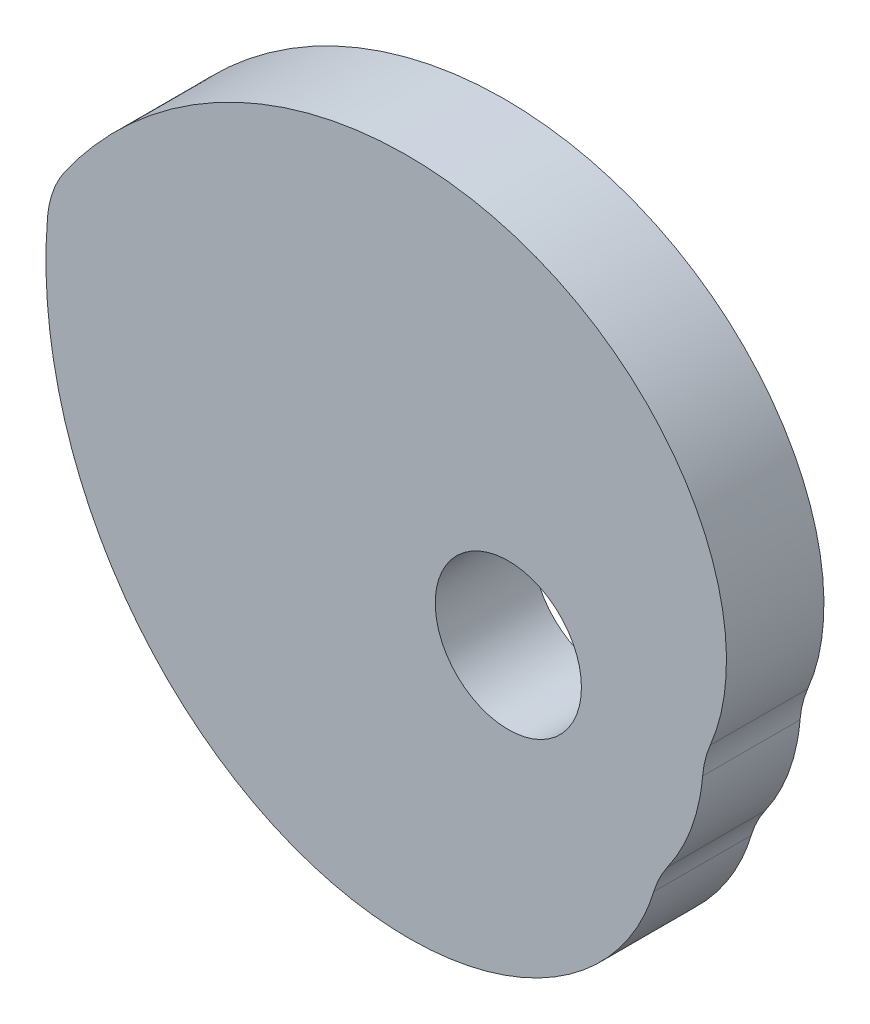
SolidWorks part; units mm, degrees
ref_plane "Front Plane" through (0, 0, 0) normal (0, 0, 1) x (1, 0, 0)
ref_plane "Top Plane" through (0, 0, 0) normal (0, 1, 0) x (1, 0, 0)
ref_plane "Right Plane" through (0, 0, 0) normal (1, 0, 0) x (0, 0, -1)
sketch "Sketch1" plane through (0, 0, 0) normal (0, 0, 1) x (1, 0, 0)
  line L0 (0, 0) -> (20, 0) construction
  line L1 (0, 0) -> (-46.9846, 17.101) construction
  line L2 (0, 0) -> (15.3209, -12.8558) construction
  circle A0 centre (0, 0) radius 7.5
  spline S0 degree 4 poles (16.3414, -4.6859) (16.584, -4.4696) (17.0571, -4.0239) (17.6514, -3.3997) (18.2682, -2.6553) (18.7157, -2.0568) (19.0176, -1.6247) (19.2223, -1.3162) (19.392, -1.0492) (19.5286, -0.827) (19.6366, -0.6464) (19.7466, -0.457) (19.8584, -0.2589) (19.9592, -0.0763) (20.0367, 0.068) (20.1296, 0.2455) (20.2275, 0.4368) (20.3208, 0.624) (20.4081, 0.8045) (20.5131, 1.0282) (20.6364, 1.3001) (20.7759, 1.6223) (20.9646, 2.0844) (21.1762, 2.6456) (21.4008, 3.3081) (21.6273, 4.0749) (21.8239, 4.8499) (21.9906, 5.6318) (22.1278, 6.4195) (22.3436, 8.0039) (22.4443, 10.0042) (22.3243, 12.2059) (21.8654, 14.9688) (21.1948, 17.4828) (20.197, 20.1038) (18.7113, 22.9431) (16.9139, 25.5954) (14.838, 28.0353) (12.4818, 30.2764) (9.9056, 32.2606) (7.1431, 33.9754) (3.5089, 35.766) (-1.0375, 37.3422) (-5.776, 38.2268) (-10.5806, 38.4309) (-14.5726, 38.1617) (-17.7384, 37.6895) (-20.8568, 36.9689) (-23.91, 36.009) (-26.8813, 34.82) (-29.7555, 33.4127) (-32.5188, 31.7986) (-34.8286, 30.2159) (-36.7241, 28.7452) (-38.2444, 27.4475) (-39.4238, 26.3678) (-40.5652, 25.2481) (-41.6677, 24.0898) (-42.5972, 23.0445) (-43.3689, 22.1259) (-44.1189, 21.1916) (-44.8497, 20.2382) (-45.4919, 19.3511) (-46.0606, 18.5223) (-46.4428, 17.946) (-46.6633, 17.6072) (-46.9425, 17.1695) (-47.0993, 16.9184) (-47.3759, 16.4693) (-47.6102, 16.0786) (-47.8551, 15.663) (-48.1353, 15.1756) (-48.4467, 14.6171) (-48.7518, 14.0529) (-49.0491, 13.4857) (-49.4119, 12.7716) (-49.8324, 11.9075) (-50.3016, 10.889) (-50.808, 9.7118) (-51.1654, 8.8196) (-51.3937, 8.2209) (-51.5053, 7.9206) knots 0 0 0 0 0 0.010945 0.021891 0.028999 0.032553 0.036108 0.039662 0.041439 0.043216 0.044993 0.04677 0.048547 0.050324 0.052007 0.05369 0.055373 0.057056 0.058739 0.060422 0.063788 0.067154 0.07052 0.077252 0.083984 0.090716 0.097448 0.10418 0.110913 0.117645 0.151305 0.171501 0.184965 0.211893 0.238822 0.26575 0.292678 0.319606 0.346534 0.375102 0.40203 0.428958 0.482814 0.536671 0.563599 0.590527 0.617455 0.644384 0.671312 0.69824 0.725168 0.752097 0.779025 0.792489 0.805953 0.819417 0.832881 0.846345 0.859809 0.866541 0.873273 0.886738 0.900202 0.903568 0.906934 0.9103 0.913666 0.919062 0.92176 0.924458 0.929854 0.935249 0.940645 0.946041 0.951437 0.956833 0.967625 0.978416 0.989208 1 1 1 1 1 construction
  spline S1 degree 4 poles (20, 0) (20.0204, 0.038) (20.0609, 0.1142) (20.1296, 0.2455) (20.2275, 0.4368) (20.3208, 0.624) (20.4081, 0.8045) (20.5131, 1.0282) (20.6364, 1.3001) (20.7759, 1.6223) (20.9646, 2.0844) (21.1762, 2.6456) (21.4008, 3.3081) (21.6273, 4.0749) (21.8239, 4.8499) (21.9906, 5.6318) (22.1278, 6.4195) (22.3436, 8.0039) (22.4443, 10.0042) (22.3243, 12.2059) (21.8654, 14.9688) (21.1948, 17.4828) (20.197, 20.1038) (18.7113, 22.9431) (16.9139, 25.5954) (14.838, 28.0353) (12.4818, 30.2764) (9.9056, 32.2606) (7.1431, 33.9754) (3.5089, 35.766) (-1.0375, 37.3422) (-5.776, 38.2268) (-10.5806, 38.4309) (-14.5726, 38.1617) (-17.7384, 37.6895) (-20.8568, 36.9689) (-23.91, 36.009) (-26.8813, 34.82) (-29.7555, 33.4127) (-32.5188, 31.7986) (-34.8286, 30.2159) (-36.7241, 28.7452) (-38.2444, 27.4475) (-39.4238, 26.3678) (-40.5652, 25.2481) (-41.6677, 24.0898) (-42.5972, 23.0445) (-43.3689, 22.1259) (-44.1189, 21.1916) (-44.8497, 20.2382) (-45.4919, 19.3511) (-46.0606, 18.5223) (-46.4428, 17.946) (-46.6633, 17.6072) (-46.8453, 17.3219) (-46.9388, 17.1741) (-46.9846, 17.101) knots 0.050324 0.050324 0.050324 0.050324 0.050324 0.052007 0.05369 0.055373 0.057056 0.058739 0.060422 0.063788 0.067154 0.07052 0.077252 0.083984 0.090716 0.097448 0.10418 0.110913 0.117645 0.151305 0.171501 0.184965 0.211893 0.238822 0.26575 0.292678 0.319606 0.346534 0.375102 0.40203 0.428958 0.482814 0.536671 0.563599 0.590527 0.617455 0.644384 0.671312 0.69824 0.725168 0.752097 0.779025 0.792489 0.805953 0.819417 0.832881 0.846345 0.859809 0.866541 0.873273 0.886738 0.900202 0.903568 0.906934 0.9103 0.913666 0.913666 0.913666 0.913666 0.913666
  spline S2 degree 4 poles (-44.5466, 27.0394) (-44.6541, 26.7376) (-44.8641, 26.1324) (-45.1139, 25.3712) (-45.3943, 24.4522) (-45.6591, 23.5279) (-45.8666, 22.7552) (-46.0613, 21.9768) (-46.2783, 21.0432) (-46.4467, 20.2549) (-46.5996, 19.4789) (-46.7426, 18.6728) (-46.8406, 18.0861) (-46.9613, 17.2788) (-47.027, 16.798) (-47.1477, 15.8345) (-47.2145, 15.1607) (-47.294, 14.2998) (-47.3463, 13.5386) (-47.393, 12.7222) (-47.4225, 11.9335) (-47.4449, 10.9307) (-47.444, 9.7354) (-47.4044, 8.3364) (-47.3045, 6.7427) (-47.1118, 4.7546) (-46.7712, 2.3821) (-46.2135, -0.3596) (-45.3559, -3.4397) (-44.4134, -6.074) (-43.4696, -8.2776) (-42.5935, -10.0723) (-41.8393, -11.4808) (-40.8307, -13.2045) (-39.5162, -15.2094) (-37.8343, -17.4457) (-35.7165, -19.8419) (-32.8364, -22.6145) (-29.0309, -25.5477) (-24.8388, -27.9189) (-20.349, -29.6385) (-16.3978, -30.6131) (-13.1609, -31.0805) (-9.8929, -31.2172) (-6.6286, -31.0109) (-3.4732, -30.474) (-0.3947, -29.5961) (2.5651, -28.375) (5.3608, -26.813) (7.7818, -25.0363) (9.9742, -22.9859) (11.6396, -20.9867) (12.7488, -19.3214) (13.5158, -17.9193) (13.9064, -17.1099) (14.1491, -16.5622) (14.3393, -16.1006) (14.4841, -15.7284) (14.6214, -15.3534) (14.751, -14.9759) (14.8731, -14.5949) (14.9873, -14.2117) (15.092, -13.8335) (15.1913, -13.4398) (15.2883, -13.0142) (15.3445, -12.7462) (15.4157, -12.3726) (15.4765, -12.0193) (15.5264, -11.688) (15.5699, -11.356) (15.6173, -10.9353) (15.6613, -10.4293) (15.6932, -9.8388) (15.7033, -9.1622) (15.6859, -8.4861) (15.6427, -7.8388) (15.5917, -7.362) (15.5506, -7.0543) (15.5303, -6.9145) knots 0 0 0 0 0 0.010792 0.021584 0.026979 0.032375 0.043167 0.048563 0.053959 0.064751 0.070146 0.075542 0.080938 0.086334 0.093061 0.099787 0.106513 0.11324 0.119966 0.126692 0.133419 0.140145 0.153598 0.167051 0.180503 0.193956 0.220861 0.247767 0.274672 0.301578 0.31503 0.328483 0.341936 0.355389 0.382294 0.4092 0.436105 0.46301 0.516821 0.570632 0.597538 0.624443 0.653716 0.680621 0.707527 0.734432 0.761338 0.788243 0.815149 0.842054 0.862233 0.889139 0.902591 0.909318 0.916044 0.919407 0.92277 0.926134 0.929497 0.93286 0.936223 0.939586 0.942949 0.946313 0.949676 0.952524 0.955371 0.958219 0.961067 0.963915 0.966763 0.972458 0.978154 0.983849 0.989545 0.995241 1 1 1 1 1 construction
  spline S3 degree 4 poles (-46.9846, 17.101) (-47.0082, 16.9303) (-47.0525, 16.5947) (-47.1477, 15.8345) (-47.2145, 15.1607) (-47.294, 14.2998) (-47.3463, 13.5386) (-47.393, 12.7222) (-47.4225, 11.9335) (-47.4449, 10.9307) (-47.444, 9.7354) (-47.4044, 8.3364) (-47.3045, 6.7427) (-47.1118, 4.7546) (-46.7712, 2.3821) (-46.2135, -0.3596) (-45.3559, -3.4397) (-44.4134, -6.074) (-43.4696, -8.2776) (-42.5935, -10.0723) (-41.8393, -11.4808) (-40.8307, -13.2045) (-39.5162, -15.2094) (-37.8343, -17.4457) (-35.7165, -19.8419) (-32.8364, -22.6145) (-29.0309, -25.5477) (-24.8388, -27.9189) (-20.349, -29.6385) (-16.3978, -30.6131) (-13.1609, -31.0805) (-9.8929, -31.2172) (-6.6286, -31.0109) (-3.4732, -30.474) (-0.3947, -29.5961) (2.5651, -28.375) (5.3608, -26.813) (7.7818, -25.0363) (9.9742, -22.9859) (11.6396, -20.9867) (12.7488, -19.3214) (13.5158, -17.9193) (13.9064, -17.1099) (14.1491, -16.5622) (14.3393, -16.1006) (14.4841, -15.7284) (14.6214, -15.3534) (14.751, -14.9759) (14.8731, -14.5949) (14.9873, -14.2117) (15.092, -13.8335) (15.1913, -13.4398) (15.2669, -13.1079) (15.3033, -12.9401) (15.3209, -12.8558) knots 0.086334 0.086334 0.086334 0.086334 0.086334 0.093061 0.099787 0.106513 0.11324 0.119966 0.126692 0.133419 0.140145 0.153598 0.167051 0.180503 0.193956 0.220861 0.247767 0.274672 0.301578 0.31503 0.328483 0.341936 0.355389 0.382294 0.4092 0.436105 0.46301 0.516821 0.570632 0.597538 0.624443 0.653716 0.680621 0.707527 0.734432 0.761338 0.788243 0.815149 0.842054 0.862233 0.889139 0.902591 0.909318 0.916044 0.919407 0.92277 0.926134 0.929497 0.93286 0.936223 0.939586 0.942949 0.946313 0.949676 0.949676 0.949676 0.949676 0.949676
  spline S4 degree 4 poles (14.3946, -13.8854) (14.4274, -13.8509) (14.491, -13.7841) (14.5948, -13.6768) (14.8025, -13.4489) (14.9529, -13.2858) (15.2555, -12.9343) (15.3819, -12.7838) (15.6632, -12.44) (15.8275, -12.2269) (16.0524, -11.9331) (16.2343, -11.682) (16.4348, -11.4001) (16.6169, -11.1316) (16.8026, -10.8503) (16.979, -10.5714) (17.1965, -10.2158) (17.4466, -9.7852) (17.7252, -9.2738) (18.0235, -8.6797) (18.3021, -8.0759) (18.5604, -7.4629) (18.7982, -6.8422) (19.0152, -6.213) (19.2112, -5.5786) (19.386, -4.9352) (19.5394, -4.291) (19.6711, -3.6344) (19.7812, -2.9865) (19.8693, -2.314) (19.9356, -1.6756) (19.9742, -1.0559) (19.9936, -0.6196) (20.0005, -0.0997) (20.0004, 0.106) (19.9946, 0.5618) (19.9842, 0.7907) (19.9715, 1.0937) (19.961, 1.2454) (19.9553, 1.3368) (19.9523, 1.3839) knots 0 0 0 0 0 0.010393 0.020785 0.041571 0.062104 0.082638 0.102512 0.122387 0.142261 0.162135 0.18201 0.201884 0.221758 0.241633 0.261507 0.281382 0.32113 0.360879 0.400628 0.440377 0.480126 0.519874 0.559623 0.599372 0.639121 0.67887 0.718618 0.758367 0.798116 0.837865 0.877613 0.897488 0.917362 0.937896 0.958429 0.979215 0.989607 1 1 1 1 1 construction
  spline S5 degree 4 poles (15.3209, -12.8558) (15.3655, -12.8026) (15.454, -12.6957) (15.6632, -12.44) (15.8275, -12.2269) (16.0524, -11.9331) (16.2343, -11.682) (16.4348, -11.4001) (16.6169, -11.1316) (16.8026, -10.8503) (16.979, -10.5714) (17.1965, -10.2158) (17.4466, -9.7852) (17.7252, -9.2738) (18.0235, -8.6797) (18.3021, -8.0759) (18.5604, -7.4629) (18.7982, -6.8422) (19.0152, -6.213) (19.2112, -5.5786) (19.386, -4.9352) (19.5394, -4.291) (19.6711, -3.6344) (19.7812, -2.9865) (19.8693, -2.314) (19.9356, -1.6756) (19.9742, -1.0559) (19.9936, -0.6196) (19.9991, -0.2064) (20, -0.0694) (20, 0) knots 0.082638 0.082638 0.082638 0.082638 0.082638 0.102512 0.122387 0.142261 0.162135 0.18201 0.201884 0.221758 0.241633 0.261507 0.281382 0.32113 0.360879 0.400628 0.440377 0.480126 0.519874 0.559623 0.599372 0.639121 0.67887 0.718618 0.758367 0.798116 0.837865 0.877613 0.897488 0.917362 0.917362 0.917362 0.917362 0.917362
  dimension "D3" = 15
  dimension "D1" = 160
  dimension "D2" = 20
extrude "Boss-Extrude2" add sketch "Sketch1" along normal blind 10
fillet "Fillet1" radius 10 3 edges at (-46.9846, 17.101, 5) (15.3209, -12.8558, 5) (20, 0, 5)
